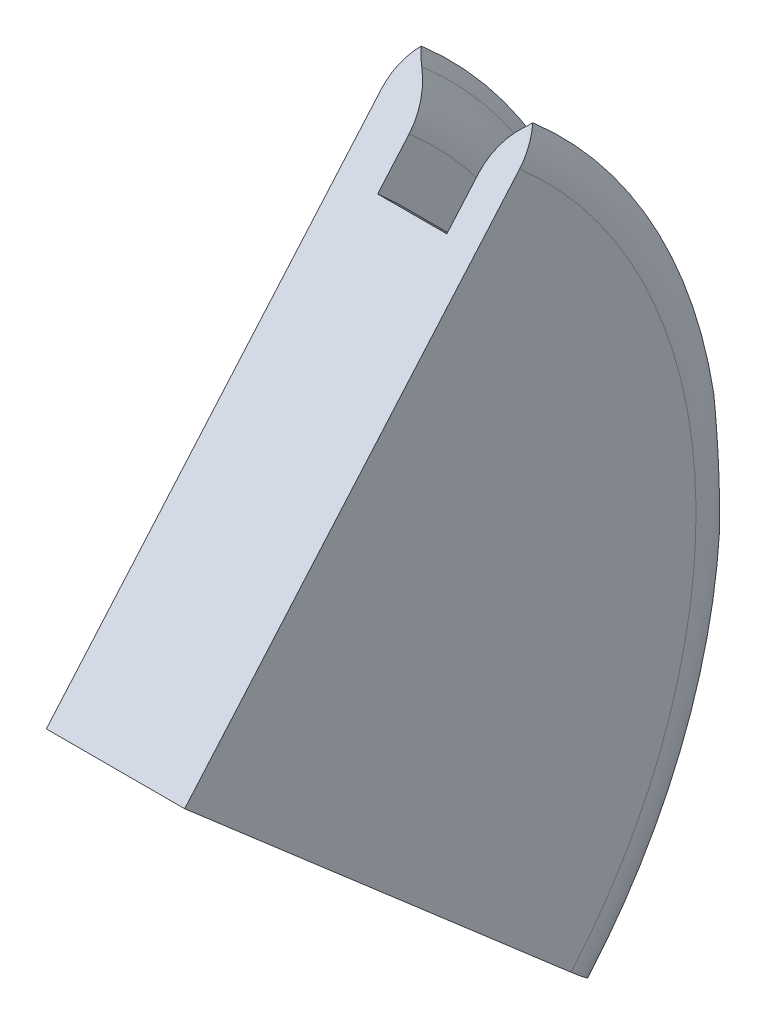
SolidWorks part; units mm, degrees
ref_plane "Front Plane" through (0, 0, 0) normal (0, 0, 1) x (1, 0, 0)
ref_plane "Top Plane" through (0, 0, 0) normal (0, 1, 0) x (1, 0, 0)
ref_plane "Right Plane" through (0, 0, 0) normal (1, 0, 0) x (0, 0, -1)
sketch "Sketch1" plane through (0, 0, 0) normal (0, 0, 1) x (1, 0, 0)
  line L0 (1, 5.5) -> (1.5, 5.5)
  line L2 (-2.5, 2) -> (-2.5, 4.5)
  line L3 (-1.5, 5.5) -> (-1, 5.5)
  line L4 (2.5, 2) -> (2.5, 4.5)
  line L6 (-1, 5.5) -> (-1, 4.9194)
  line L7 (-1, 4.9194) -> (1, 4.9194)
  line L8 (1, 5.5) -> (1, 4.9194)
  line L9 (-2.5, 2) -> (2.5, 2)
  line L10 (0, 0) -> (6.5963, 0) construction
  line L11 (-2.5, 4.5) -> (-1.5, 5.5)
  line L12 (1.5, 5.5) -> (2.5, 4.5)
  point P1 (2.5, 5.5)
  point P2 (-2.5, 5.5)
  dimension "D1" = 5.5
  dimension "D3" = 2
sketch "Sketch2" plane through (0, 0, 0) normal (0, 1, 0) x (1, 0, 0)
  line L0 (-1, 0) -> (1, 0) construction
  line L1 (-1, 0) -> (1, 0)
  line L3 (-1, 5.5) -> (-1, 0)
  line L5 (1, 5.5) -> (1, 0)
  line L8 (-1, 5.5) -> (-1, 7.3953)
  line L10 (1, 5.5) -> (1, 7.3953)
  line L11 (-0.4305, 7.1414) -> (-0.4305, 6.4476)
  line L12 (-0.4305, 6.4476) -> (0.5695, 6.4476)
  line L13 (0.5695, 7.1414) -> (0.5695, 6.4476)
  line L14 (0.0695, 7.4657) -> (0.5695, 6.4476) construction
  line L15 (-0.4305, 6.4476) -> (0.0695, 7.4657) construction
  arc A0 (1, 7.3953) -> (0.8776, 7.8747) centre (0, 7.3953) ccw
  arc A2 (-0.8083, 7.984) -> (-1, 7.3953) centre (0, 7.3953) ccw
  arc A3 (0.5695, 7.1414) -> (0.8205, 7.804) centre (1.5695, 7.1414) cw
  arc A4 (-0.4305, 7.1414) -> (-0.6814, 7.804) centre (-1.4305, 7.1414) ccw
  ellipse E0 centre (0.0695, 8.4674) end of major axis (-0.9328, 8.4674) minor radius 1.0017 (0.8205, 7.804) -> (0.8776, 7.8747) ccw
  ellipse E2 centre (0.0695, 8.4674) end of major axis (-0.9328, 8.4674) minor radius 1.0017 (-0.8083, 7.984) -> (-0.6814, 7.804) ccw
  point P4 (0.0695, 7.4657)
  dimension "D1" = 1
revolve "Revolve1" add sketch "Sketch2" angle 360 about L10
sketch "Sketch3" plane through (0, 0, 0) normal (1, 0, 0) x (0, 0, -1)
  line L0 (0, 0) -> (7.4129, 8.5556)
  line L1 (0, 0) -> (8.1849, -7.0916)
  line L2 (7.4129, 8.5556) -> (8.1849, -7.0916)
extrude "Cut-Extrude1" cut sketch "Sketch3" against normal through all both and the other way through all flip side to cut
